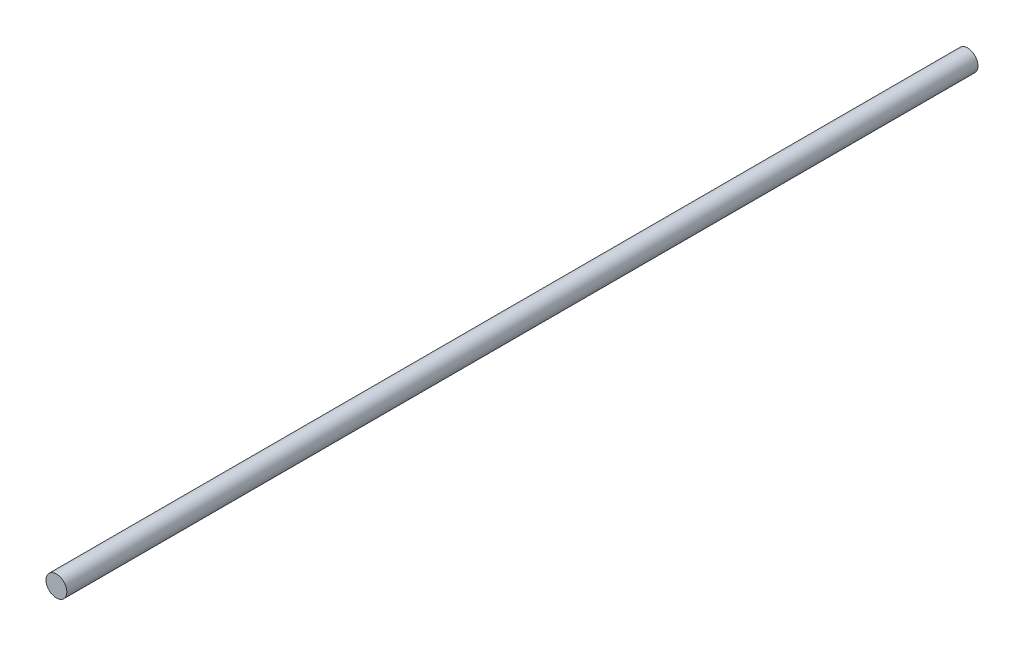
SolidWorks part; units mm, degrees
ref_plane "前视基准面" through (0, 0, 0) normal (0, 0, 1) x (1, 0, 0)
ref_plane "上视基准面" through (0, 0, 0) normal (0, 1, 0) x (1, 0, 0)
ref_plane "右视基准面" through (0, 0, 0) normal (1, 0, 0) x (0, 0, -1)
sketch "草图1" plane through (0, 0, 0) normal (0, 0, 1) x (1, 0, 0)
  circle A0 centre (0, 0) radius 4
  dimension "D1" = 8
extrude "凸台-拉伸1" add sketch "草图1" along normal mid plane 350
